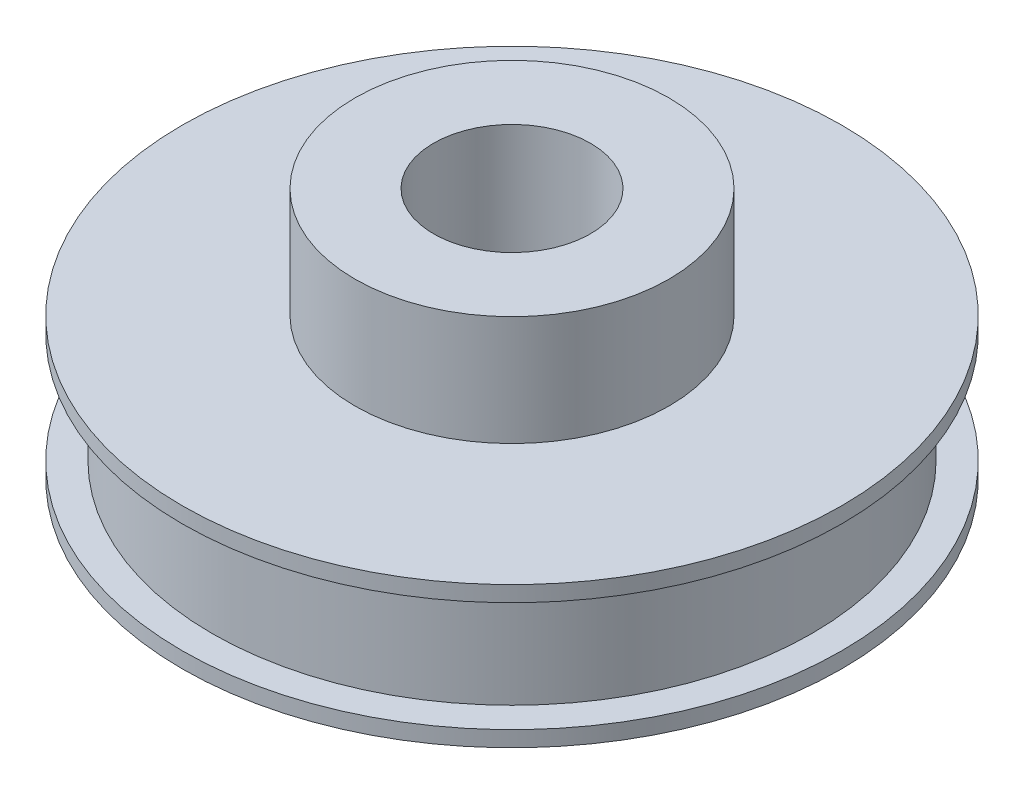
SolidWorks part; units mm, degrees
ref_plane "Front Plane" through (0, 0, 0) normal (0, 0, 1) x (1, 0, 0)
ref_plane "Top Plane" through (0, 0, 0) normal (0, 1, 0) x (1, 0, 0)
ref_plane "Right Plane" through (0, 0, 0) normal (1, 0, 0) x (0, 0, -1)
sketch "Sketch1" plane through (0, 0, 0) normal (0, 0, 1) x (1, 0, 0)
  line L0 (0, 0) -> (0, 16) construction
  line L1 (5, 16) -> (10, 16)
  line L2 (10, 16) -> (10, 9)
  line L3 (10, 9) -> (21, 9)
  line L4 (21, 9) -> (21, 8)
  line L5 (21, 8) -> (19.1, 8)
  line L6 (19.1, 8) -> (19.1, 1)
  line L7 (19.1, 1) -> (21, 1)
  line L8 (21, 1) -> (21, 0)
  line L9 (21, 0) -> (5, 0)
  line L11 (5, 16) -> (5, 0)
  dimension "D1" = 16
  dimension "D2" = 1
  dimension "D3" = 42
  dimension "D4" = 38.2
  dimension "D5" = 7
  dimension "D6" = 20
  dimension "D7" = 10
revolve "Revolve1" add sketch "Sketch1" angle 360 about L0
